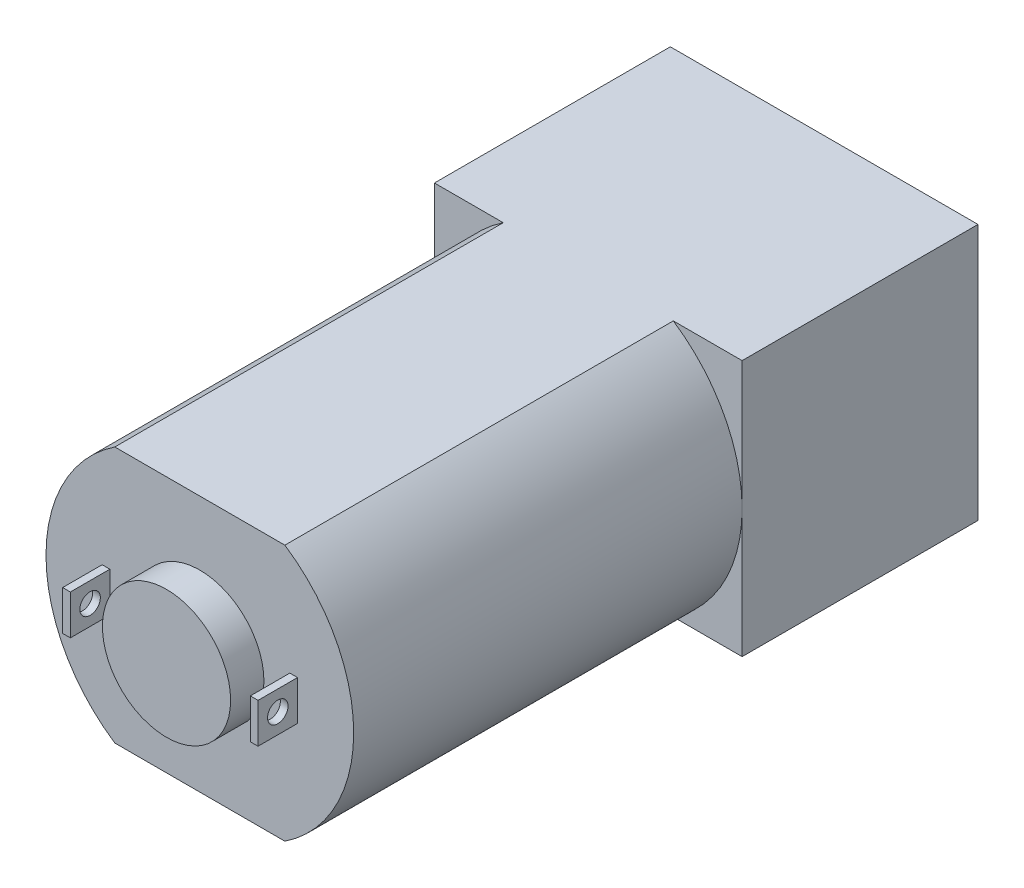
SolidWorks part; units mm, degrees
ref_plane "Front Plane" through (0, 0, 0) normal (0, 0, 1) x (1, 0, 0)
ref_plane "Top Plane" through (0, 0, 0) normal (0, 1, 0) x (1, 0, 0)
ref_plane "Right Plane" through (0, 0, 0) normal (1, 0, 0) x (0, 0, -1)
sketch "Sketch1" plane through (0, 0, 0) normal (0, 0, 1) x (1, 0, 0)
  line L0 (-85.2212, 0) -> (91.7733, 0) construction
  line L1 (3.3166, 5) -> (-3.3166, 5)
  line L2 (3.3166, -5) -> (-3.3166, -5)
  arc A0 (-3.3166, 5) -> (-3.3166, -5) centre (0, 0) ccw
  arc A1 (3.3166, -5) -> (3.3166, 5) centre (0, 0) ccw
  dimension "D2" = 6
  dimension "D1" = 10
extrude "Boss-Extrude1" add sketch "Sketch1" along normal blind 15.15
sketch "Sketch2" plane through (0, 0, 15.15) normal (0, 0, 1) x (1, 0, 0)
  line L0 (-1.118, 1) -> (1.118, 1)
  arc A0 (-1.118, 1) -> (1.118, 1) centre (0, 0) ccw
  dimension "D1" = 3
  dimension "D2" = 1
sketch "Sketch3" plane through (0, 0, 0) normal (0, 0, -1) x (-1, 0, 0)
  line L0 (-3.3166, 5) -> (3.3166, 5) construction
  line L1 (-6, 5) -> (6, 5)
  line L2 (-6, 5) -> (-6, -5)
  line L3 (-6, -5) -> (6, -5)
  line L4 (6, 5) -> (6, -5)
  line L5 (3.3166, -5) -> (-3.3166, -5) construction
  arc A0 (3.3166, -5) -> (3.3166, 5) centre (0, 0) ccw construction
  arc A1 (-3.3166, 5) -> (-3.3166, -5) centre (0, 0) ccw construction
extrude "Boss-Extrude2" add sketch "Sketch3" along normal blind 9.2
sketch "Sketch4" plane through (0, 0, 15.15) normal (0, 0, 1) x (1, 0, 0)
  circle A0 centre (0, 0) radius 2.5
  dimension "D1" = 5
extrude "Boss-Extrude3" add sketch "Sketch4" along normal blind 1.3
sketch "Sketch5" plane through (0, 0, 15.15) normal (0, 0, 1) x (1, 0, 0)
  line L0 (0, 0) -> (0, 2.9007) construction
  line L1 (-3.81, 0.775) -> (-3.51, 0.775)
  line L2 (-3.81, 0.775) -> (-3.81, -0.775)
  line L3 (-3.81, -0.775) -> (-3.51, -0.775)
  line L4 (-3.51, 0.775) -> (-3.51, -0.775)
  line L5 (0, 2.9007) -> (-3.4744, 5.4378) construction
  line L6 (3.51, 0.775) -> (3.51, -0.775)
  line L7 (3.81, -0.775) -> (3.51, -0.775)
  line L8 (3.81, 0.775) -> (3.81, -0.775)
  line L9 (3.81, 0.775) -> (3.51, 0.775)
  line L10 (0, 0) -> (-2.0523, 0) construction
  point P12 (-3.81, 0)
  dimension "D1" = 1.55
  dimension "D2" = 0.3
  dimension "D3" = 7.62
extrude "Boss-Extrude4" add sketch "Sketch5" along normal blind 1.54 separate body
sketch "Sketch6" plane through (-3.81, 0, 0) normal (-1, 0, 0) x (0, 0, 1)
  line L1 (15.15, 0.775) -> (16.69, -0.775) construction
  line L2 (16.69, -0.775) -> (15.15, -0.775) construction
  circle A0 centre (15.92, 0) radius 0.4
  dimension ".8" = 0.8
extrude "Cut-Extrude1" cut sketch "Sketch6" against normal up to next (0.3 mm away)
sketch "Sketch7" plane through (3.51, 0, 0) normal (-1, 0, 0) x (0, 0, 1)
  circle A0 centre (15.92, 0) radius 0.4 construction
  circle A1 centre (15.92, 0) radius 0.4
extrude "Cut-Extrude2" cut sketch "Sketch7" against normal up to next (0.3 mm away)
sketch "Sketch8" plane through (0, 0, -9.2) normal (0, 0, -1) x (-1, 0, 0)
  circle A0 centre (0, 0) radius 2
  dimension "D1" = 4
extrude "Boss-Extrude5" add sketch "Sketch8" along normal blind 0.7
